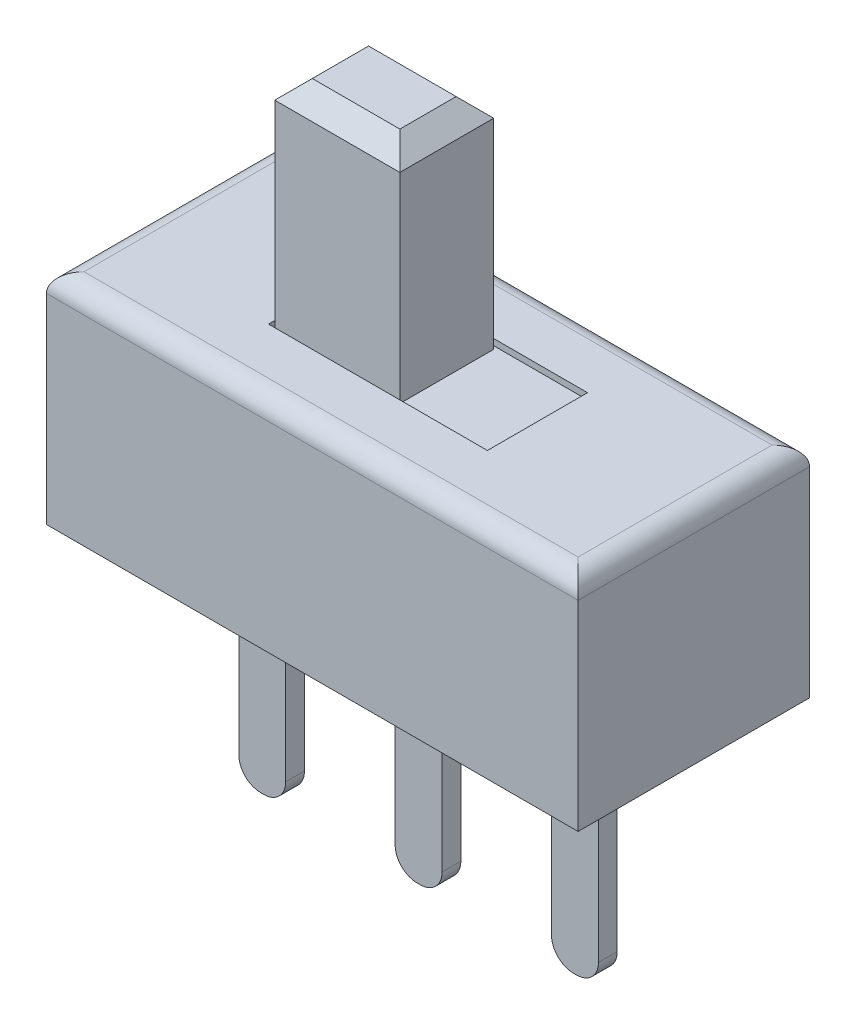
SolidWorks part; units mm, degrees
ref_plane "Front Plane" through (0, 0, 0) normal (0, 0, 1) x (1, 0, 0)
ref_plane "Top Plane" through (0, 0, 0) normal (0, 1, 0) x (1, 0, 0)
ref_plane "Right Plane" through (0, 0, 0) normal (1, 0, 0) x (0, 0, -1)
sketch "Sketch1" plane through (0, 0, 0) normal (0, 1, 0) x (1, 0, 0)
  line L1 (-4.25, -1.85) -> (4.25, -1.85)
  line L2 (-4.25, -1.85) -> (-4.25, 1.85)
  line L3 (-4.25, 1.85) -> (4.25, 1.85)
  line L4 (4.25, -1.85) -> (4.25, 1.85)
  line L5 (-4.25, -1.85) -> (4.25, 1.85) construction
  line L6 (-4.25, 1.85) -> (4.25, -1.85) construction
  point P0 (0, 0)
  dimension "D1" = 8.5
  dimension "D2" = 3.7
extrude "Boss-Extrude1" add sketch "Sketch1" along normal mid plane 3.5
sketch "Sketch2" plane through (0, 1.75, 0) normal (0, 1, 0) x (1, 0, 0)
  line L1 (-1.75, -0.8) -> (1.75, -0.8)
  line L2 (-1.75, -0.8) -> (-1.75, 0.8)
  line L3 (-1.75, 0.8) -> (1.75, 0.8)
  line L4 (1.75, -0.8) -> (1.75, 0.8)
  line L5 (-1.75, -0.8) -> (1.75, 0.8) construction
  line L6 (-1.75, 0.8) -> (1.75, -0.8) construction
  point P0 (0, 0)
  dimension "D1" = 3.5
  dimension "D2" = 1.6
extrude "Cut-Extrude1" cut sketch "Sketch2" against normal blind 0.1
sketch "Sketch3" plane through (0, 1.65, 0) normal (0, 1, 0) x (1, 0, 0)
  line L0 (-1.7, -0.75) -> (0.3, 0.75) construction
  line L1 (-1.7, 0.75) -> (0.3, 0.75)
  line L2 (-1.7, 0.75) -> (-1.7, -0.75)
  line L3 (-1.7, -0.75) -> (0.3, -0.75)
  line L4 (0.3, 0.75) -> (0.3, -0.75)
  line L5 (-1.75, 0) -> (1.75, 0) construction
  line L6 (-1.75, 0.8) -> (-1.75, -0.8) construction
  line L7 (1.75, -0.8) -> (1.75, 0.8) construction
  point P10 (-0.7, 0)
  dimension "D1" = 1.5
  dimension "D2" = 2
  dimension "D3" = 0.05
extrude "Boss-Extrude2" add sketch "Sketch3" along normal blind 3.5
sketch "Sketch4" plane through (0, -1.75, 0) normal (0, -1, 0) x (1, 0, 0)
  line L0 (-4.25, 0) -> (4.25, 0) construction
  line L1 (-4.25, -1.85) -> (-4.25, 1.85) construction
  line L2 (4.25, 1.85) -> (4.25, -1.85) construction
  line L3 (0, 1.85) -> (0, -1.85) construction
  line L4 (-0.375, 0.15) -> (0.375, 0.15)
  line L5 (-0.375, 0.15) -> (-0.375, -0.15)
  line L6 (-0.375, -0.15) -> (0.375, -0.15)
  line L7 (0.375, 0.15) -> (0.375, -0.15)
  line L8 (-0.375, 0.15) -> (0.375, -0.15) construction
  line L9 (-0.375, -0.15) -> (0.375, 0.15) construction
  line L10 (-2.875, 0.15) -> (-2.125, 0.15)
  line L11 (-2.875, 0.15) -> (-2.875, -0.15)
  line L12 (-2.875, -0.15) -> (-2.125, -0.15)
  line L13 (-2.125, 0.15) -> (-2.125, -0.15)
  line L14 (-2.875, 0.15) -> (-2.125, -0.15) construction
  line L15 (-2.875, -0.15) -> (-2.125, 0.15) construction
  line L16 (-4.25, 1.85) -> (4.25, 1.85) construction
  line L17 (4.25, -1.85) -> (-4.25, -1.85) construction
  line L18 (2.125, 0.15) -> (2.125, -0.15)
  line L19 (2.875, -0.15) -> (2.125, -0.15)
  line L20 (2.875, 0.15) -> (2.875, -0.15)
  line L21 (2.875, 0.15) -> (2.125, 0.15)
  point P6 (0, 0)
  point P11 (-2.5, 0)
  dimension "D1" = 0.3
  dimension "D2" = 0.75
  dimension "D3" = 0.75
  dimension "D4" = 0.3
  dimension "D5" = 2.5
extrude "Boss-Extrude3" add sketch "Sketch4" along normal blind 3.7
chamfer "Chamfer1" distance 0.3 angle 45 4 edges at (-1.7, 5.15, 0) (-0.7, 5.15, -0.75) (0.3, 5.15, 0) (-0.7, 5.15, 0.75)
fillet "Fillet1" radius 0.3 4 edges at (4.25, 1.75, 0) (0, 1.75, -1.85) (-4.25, 1.75, 0) (0, 1.75, 1.85)
fillet "Fillet2" radius 0.35 6 edges at (2.875, -5.45, 0) (2.125, -5.45, 0) (0.375, -5.45, 0) (-0.375, -5.45, 0) (-2.125, -5.45, 0) (-2.875, -5.45, 0)
